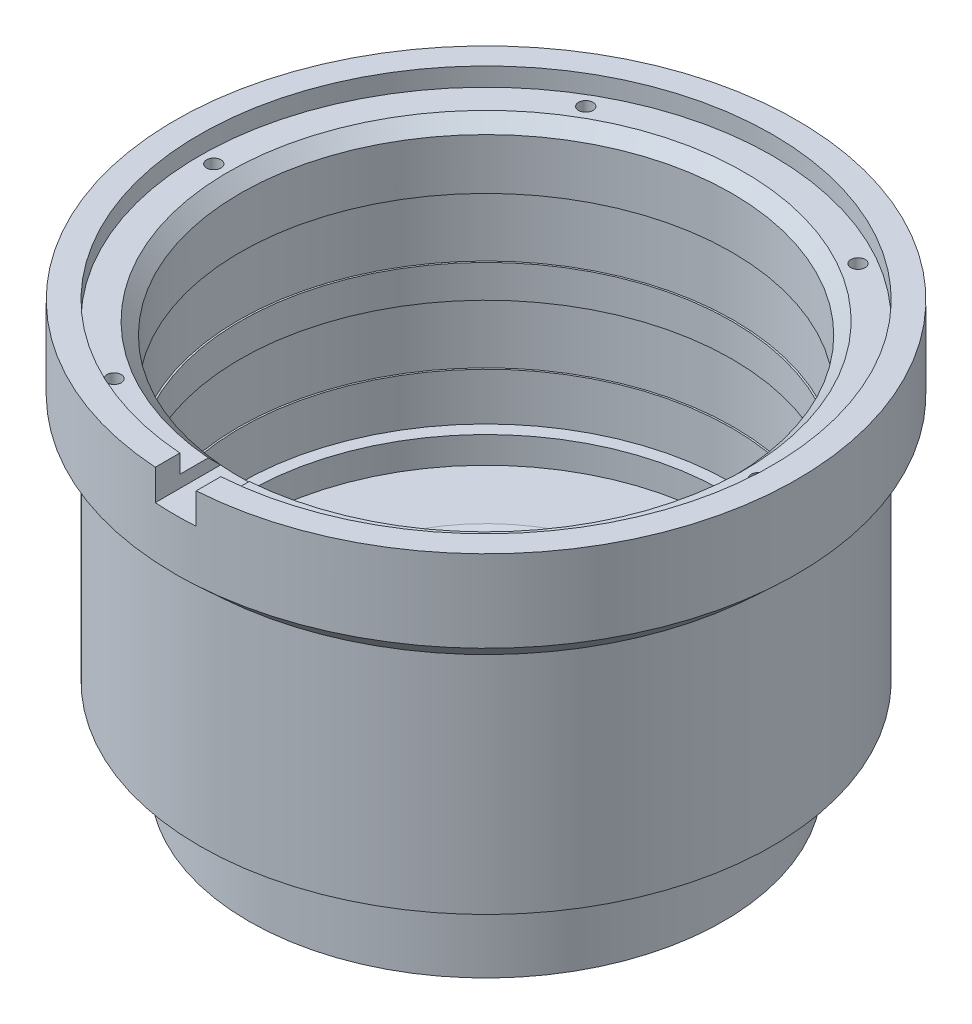
SolidWorks part; units mm, degrees
material "1060 Alloy"
ref_plane "Front Plane" through (0, 0, 0) normal (0, 0, 1) x (1, 0, 0)
ref_plane "Top Plane" through (0, 0, 0) normal (0, 1, 0) x (1, 0, 0)
ref_plane "Right Plane" through (0, 0, 0) normal (1, 0, 0) x (0, 0, -1)
sketch "Sketch7" plane through (0, 0, 0) normal (0, 0, 1) x (1, 0, 0)
  line L0 (0, -30.2319) -> (0, 30.2319) construction
  line L1 (-38, 38.06) -> (-35, 38.06)
  line L2 (-35, 38.06) -> (-35, 35.81)
  line L3 (-35, 35.81) -> (-30.0375, 35.81)
  line L7 (-9, 0) -> (-29.075, 0)
  line L10 (-38, 3.255) -> (-38, 38.06)
  line L13 (-30.0375, 35.81) -> (-30.0375, 3.255)
  line L14 (-30.0375, 3.255) -> (-29.075, 3.255)
  line L15 (-29.075, 3.255) -> (-29.075, 0)
  line L16 (-9, 0) -> (-9, -2.94)
  line L17 (-12, -13.19) -> (-38, -13.19)
  line L18 (-38, -13.19) -> (-38, 3.255)
  line L19 (-9, -2.94) -> (-12, -2.94)
  line L20 (-12, -2.94) -> (-12, -13.19)
  point P4 (0, 0)
  point P20 (-32.5187, 35.81)
  dimension "D2" = 2.25
  dimension "D3" = 4.9625
  dimension "D5" = 35.81
  dimension "D4" = 30.0375
  dimension "D8" = 32.555
  dimension "D10" = 0.9625
  dimension "D12" = 38
  dimension "D13" = 51.25
  dimension "D9" = 12
  dimension "D14" = 9
  dimension "D6" = 10.25
revolve "Base Motor Housing" add sketch "Sketch7" angle 360 about L0
chamfer "Top Chamfer" distance 1.5 angle 45 1 edges at (0, 35.81, -30.0375)
chamfer "Back Chamfer" distance 2 angle 80 1 edges at (0, 0, -9)
ref_plane "Chamfer plane" through (0, 34.31, 0) normal (0, -1, 0) x (-1, 0, 0)
sketch "Sketch8" plane through (0, 38.06, 0) normal (0, 1, 0) x (1, 0, 0)
  line L0 (0, 0) -> (0, -38) construction
  line L1 (-2.5, -38) -> (2.5, -38)
  line L2 (-2.5, -38) -> (-2.5, -29.9333)
  line L3 (-2.5, -29.9333) -> (2.5, -29.9333)
  line L4 (2.5, -38) -> (2.5, -29.9333)
  circle A0 centre (0, 0) radius 38 construction
  circle A2 centre (0, 0) radius 30.0375 construction
  point P10 (0, -38)
  dimension "D1" = 5
extrude "Wire Hole" cut sketch "Sketch8" against normal up to surface (3.75 mm away)
sketch "Sketch9" plane through (0, 35.81, 0) normal (0, 1, 0) x (1, 0, 0)
  line L0 (-31.5375, 0) -> (-35, 0) construction
  line L1 (-2.5, -34.9106) -> (-2.5, -31.4383) construction
  line L2 (-2.5, -29.9333) -> (-2.5, -37.9177) construction
  circle A2 centre (0, 0) radius 33.2688 construction
  circle A3 centre (-33.2688, 0) radius 0.875
  circle A4 centre (-16.6344, 28.8116) radius 0.875
  circle A5 centre (16.6344, 28.8116) radius 0.875
  circle A6 centre (33.2688, 0) radius 0.875
  circle A7 centre (16.6344, -28.8116) radius 0.875
  circle A8 centre (-16.6344, -28.8116) radius 0.875
  arc A9 (2.5, -34.9106) -> (-2.5, -34.9106) centre (0, 0) ccw construction
  arc A10 (2.5, -34.9106) -> (-2.5, -34.9106) centre (0, 0) ccw construction
  arc A11 (2.5, -31.4383) -> (-2.5, -31.4383) centre (0, 0) ccw construction
  arc A14 (2.5, -31.4383) -> (-2.5, -31.4383) centre (0, 0) ccw construction
  point P21 (0, 0)
  point P31 (-33.2688, 0)
  dimension "D2" = 1.75
  dimension "D3" = 6
extrude "Front-Holes" cut sketch "Sketch9" against normal blind 6
sketch "Sketch10" plane through (0, -13.19, 0) normal (0, -1, 0) x (1, 0, 0)
  line L0 (-12, 0) -> (-38, 0) construction
  circle A2 centre (0, 0) radius 12 construction
  circle A3 centre (0, 0) radius 38 construction
  circle A4 centre (-25, 0) radius 1.375
  circle A5 centre (-12.5, 21.6506) radius 1.375
  circle A6 centre (12.5, 21.6506) radius 1.375
  circle A7 centre (25, 0) radius 1.375
  circle A8 centre (12.5, -21.6506) radius 1.375
  circle A9 centre (-12.5, -21.6506) radius 1.375
  circle A10 centre (0, 0) radius 25 construction
  circle A13 centre (0, 0) radius 38 construction
  point P22 (0, 0)
  dimension "D1" = 2.75
  dimension "D2" = 6
extrude "Back-Holes" cut sketch "Sketch10" against normal blind 5
sketch "Sketch11" plane through (0, 0, 0) normal (0, 0, 1) x (1, 0, 0)
  line L0 (29, -13.19) -> (29, -5.69)
  line L3 (38, -13.19) -> (38, 38.06) construction
  line L4 (38, 28.06) -> (38, -13.19)
  line L5 (38, -13.19) -> (29, -13.19)
  line L6 (0, -8.19) -> (26.375, -8.19) construction
  line L7 (26.375, -8.19) -> (26.375, 38.06) construction
  line L8 (35, 38.06) -> (-35, 38.06) construction
  line L9 (29, -5.69) -> (38, -5.69) construction
  line L10 (0, 0) -> (0, -13.4206) construction
  line L11 (29, -5.69) -> (35, -2.2259)
  line L12 (35, -2.2259) -> (35, 25.2741)
  line L13 (35, 25.2741) -> (38, 28.06)
  line L14 (35, 25.2741) -> (37.9362, 25.2741) construction
  line L15 (-38, -13.19) -> (38, -13.19) construction
  line L19 (30.0375, 3.255) -> (-30.0375, 3.255) construction
  line L23 (30.0375, 3.255) -> (-30.0375, 3.255) construction
  dimension "D3" = 7.5
  dimension "D2" = 30
  dimension "D1" = 35
  dimension "D5" = 29
  dimension "D6" = 27.5
  dimension "D4" = 10
revolve "Lightening Cut" cut sketch "Sketch11" angle 360 about L10
sketch "Sketch12" plane through (0, 0, 0) normal (0, 0, 1) x (1, 0, 0)
  line L0 (-30.0375, 3.255) -> (-30.7875, 3.255)
  line L1 (30.0375, 3.255) -> (-30.0375, 3.255) construction
  line L2 (-30.7875, 3.255) -> (-30.0375, 3.688)
  line L3 (-30.0375, 3.688) -> (-30.0375, 3.255)
  line L4 (0, -4.2819) -> (0, 6.8752) construction
  line L5 (30.0375, 3.255) -> (-30.0375, 3.255) construction
  dimension "D1" = 0.75
  dimension "D2" = 30
revolve "Undercut for Stator" cut sketch "Sketch12" angle 360 about L4
thread "Thread1" [suppressed] pitch 0.4 start angle 0, offset 0, length 0, pitch 0.4, diameter 1.75
ref_plane "Plane1" through (-34.1438, 35.81, 0) normal (0, 0, 1) x (-1, 0, 0)
sketch "Thread Profile1" plane through (-34.1438, 35.81, 0) normal (0, 0, 1) x (-1, 0, 0)
  line L0 (0, 0) -> (0, 0.4) construction
  line L1 (0, 0) -> (0.2165, 0.125)
  line L2 (0.2165, 0.125) -> (0.2165, 0.175)
  line L3 (0.2165, 0.175) -> (0, 0.3)
  line L4 (0.2165, 0.15) -> (0, 0.15) construction
  line L11 (0, 0) -> (0, 0.3)
  point P2 (0, 0)
  dimension "Pitch" = 0.4
  dimension "Profile_Angle" = 60
  dimension "Profile_Land" = 0.05
  dimension "Profile_Height" = 0.2165
thread "Thread2" [suppressed] pitch 0.5 start angle 0, offset 0, length 0, pitch 0.5, diameter 2.75
ref_plane "Plane3" through (-23.625, -13.19, 0) normal (0, 0, 1) x (1, 0, 0)
sketch "Thread Profile3" plane through (-23.625, -13.19, 0) normal (0, 0, 1) x (1, 0, 0)
  line L0 (0, 0) -> (0, 0.5) construction
  line L1 (0, 0) -> (0.2706, 0.1562)
  line L2 (0.2706, 0.1562) -> (0.2706, 0.2187)
  line L3 (0.2706, 0.2187) -> (0, 0.375)
  line L4 (0.2706, 0.1875) -> (0, 0.1875) construction
  line L11 (0, 0) -> (0, 0.375)
  point P2 (0, 0)
  dimension "Pitch" = 0.5
  dimension "Profile_Angle" = 60
  dimension "Profile_Land" = 0.0625
  dimension "Profile_Height" = 0.2706
pattern_circular "CirPattern1" [suppressed] count 6 over 360
ref_plane "Plane4" through (0, 18.7825, 0) normal (0, -1, 0) x (-1, 0, 0)
sketch "Sketch14" plane through (0, 0, 0) normal (0, 0, 1) x (1, 0, 0)
  line L0 (-30.0375, 28.0847) -> (-30.2475, 28.0847)
  line L2 (0, -10.4986) -> (0, 5.9571) construction
  line L3 (-30.2475, 28.0847) -> (-30.2475, 20.7825)
  line L4 (-30.2475, 20.7825) -> (-30.0375, 20.7825)
  line L5 (-30.0375, 28.0847) -> (-30.0375, 20.7825)
  line L6 (-33.8663, 18.7825) -> (33.8663, 18.7825) construction
  line L7 (-30.0375, 9.4803) -> (-30.2475, 9.4803)
  line L8 (-30.2475, 16.7825) -> (-30.0375, 16.7825)
  line L9 (-30.2475, 9.4803) -> (-30.2475, 16.7825)
  line L10 (-30.0375, 9.4803) -> (-30.0375, 16.7825)
  dimension "D1" = 30.0375
  dimension "D2" = 0.21
  dimension "D3" = 2
  dimension "D4" = 7.3022
revolve "Adhesive Trench" cut sketch "Sketch14" angle 360 about L2
equation "\"D2@Sketch9\"=\"Back_mount_hole\""
equation "\"Stator_OD\"= 60'No Tolerance given"
equation "\"A\"=35.81 'taken off spec sheet for 06808 (A)"
equation "\"Rotor_ID\"= 30'No Tolerance Given"
equation "\"back_bearing_Thickness\"= 5'-0.12"
equation "\"back_bearing_OD\"= 24'-0.009 https://www.mcmaster.com/5972K155/"
equation "\"D5@Sketch7\"=\"A\""
equation "\"Stator_Gap\"= 0.0375'+- 0.0125 (From 1.3.3.1 Kollmorgen manual)"
equation "\"Back_mount_hole\"= 1.75'To be tapped to M2 (USE LOCKTITE)"
equation "\"D1@Back-Holes\" = \"back_bearing_Thickness\""
equation "\"facePlate_Mount_Hole\"= 2.75'To be tapped to M3"
equation "\"D1@Sketch10\"=\"facePlate_Mount_Hole\""
equation "\"final_shaftD\"= 12'To fit in harmonic"
equation "\"back_bearing_ID\"= 15'"
equation "\"final_shaftL\"= 5.25+3+\"sheet_thick\"+\"connector_thick\"-3+\"harmon_coupleL\"+0.5-\"shaft_Ladjust\"'length to make everything nice and aligned"
equation "\"back_bearing_IDOD\"= 16.5'measured off CAD, actually 16.75, but rounded down to nicer number"
equation "\"rotor_shaftD\"= \"Rotor_ID\" - (\"rotor-shaft_gap\")*2'"
equation "\"front_bearing_ID\"= 12'https://www.mcmaster.com/5972K154/"
equation "\"front_bearing_OD\"= 21'-0.009"
equation "\"front_bearing_IDOD\"= 13.5'Measured off CAD. Actually 13.75, but rounded down"
equation "\"front_bearing_Thickness\"= 5'-0.12"
equation "\"rotor_thickness\"= 2.4'measured off CAD"
equation "\"rotor_height\"= 32.86'+-0.075 taken off spec sheet for 06826 (C)"
equation "\"D4@Sketch7\"=\"Stator_OD\"/2+\"Stator_Gap\""
equation "\"B\"= 26.3'+-0.35 taken off spec sheet for 06826"
equation "\"D8@Sketch7\"=(\"A\"-\"B\")/2+\"B\"+1.5"
equation "\"D3@Sketch11\"=\"back_bearing_Thickness\"*1.5"
equation "\"rotor-shaft_gap\" = 0.0185 '+-0.0065 (from manual)"
equation "\"D9@Sketch7\"=\"back_bearing_OD\"/2"
equation "\"D14@Sketch7\"=\"back_bearing_OD\"/2-3"
equation "\"D6@Sketch7\"= \"back_bearing_Thickness\" + 5.25"
equation "\"D3@Sketch7\"=5-\"Stator_Gap\""
equation "\"D10@Sketch7\"=1-\"Stator_Gap\""
equation "\"D1@Sketch14\"=\"Stator_OD\"/2+\"Stator_Gap\""
equation "\"D4@Sketch14\"=\"rotor_height\"/4.5"
equation "\"key_L\"= 20'-0.2 https://www.mcmaster.com/2977N19/"
equation "\"key_H\"= 4'-0.03"
equation "\"key_W\"= 4'-0.03"
equation "\"harmon_keyH\"= 13.8'+0.1 from drawing"
equation "\"harmon_coupleL\"= 21.5' taken from drawing https://www.harmonicdrive.net/_hd/content/caddownloads/dxf/csf-2uh-ulw_gearheads/CSF-17-xxx-2UH-ULW.pdf"
equation "\"harmon_diam\"= 81' from drawing"
equation "\"harmon_BCD\"= 74.5' from drawing"
equation "\"harmon_holeD1\"= 3.4' from drawing"
equation "\"harmon_holeD2\"= 3' from drawing"
equation "\"harmon_holeAng\"= 18' from drawing"
equation "\"sheet_thick\"= 1/8*25.4 'random, replace w actual sheet thickness when u feel like :)"
equation "\"nut-thickness\"= 5 'idk measure the ones in the shop and adjust"
equation "\"connector_thick\"= 10' random for now"
equation "\"shaft_Ladjust\"= 6.75' sorry. It's silly, but it works."
